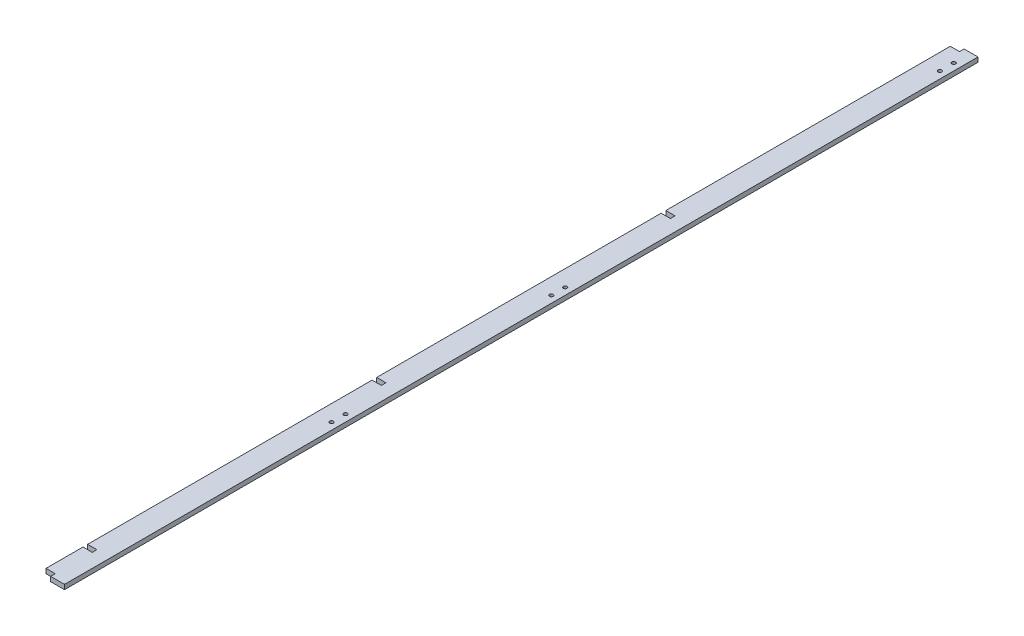
SolidWorks part; units mm, degrees
material "轻木"
ref_plane "前视基准面" through (0, 0, 0) normal (0, 0, 1) x (1, 0, 0)
ref_plane "上视基准面" through (0, 0, 0) normal (0, 1, 0) x (1, 0, 0)
ref_plane "右视基准面" through (0, 0, 0) normal (1, 0, 0) x (0, 0, -1)
other "Configuration Table"
sketch "草图1" plane through (0, 0, 1160.01) normal (0, 0, 1) x (1, 0, 0)
  line L1 (130.7876, -3.3897) -> (120.7876, -3.3897)
  line L2 (130.7876, -3.3897) -> (130.7876, -5.3897)
  line L3 (130.7876, -5.3897) -> (120.7876, -5.3897)
  line L4 (120.7876, -3.3897) -> (120.7876, -5.3897)
  dimension "D1" = 2
  dimension "D2" = 10
extrude "凸台-拉伸1" add sketch "草图1" against normal blind 395
sketch "草图2" plane through (0, -3.3897, 0) normal (0, 1, 0) x (1, 0, 0)
  line L0 (120.7876, -890.01) -> (124.7876, -890.01)
  line L9 (120.7876, -890.01) -> (120.7876, -892.01)
  line L22 (120.7876, -892.01) -> (124.7876, -892.01)
  line L23 (120.7876, -765.01) -> (124.7876, -765.01)
  line L28 (120.7876, -765.01) -> (120.7876, -767.01)
  line L29 (120.7876, -767.01) -> (124.7876, -767.01)
  line L30 (124.7876, -890.01) -> (124.7876, -892.01)
  line L39 (124.7876, -765.01) -> (124.7876, -767.01)
  line L40 (120.7876, -1015.01) -> (124.7876, -1015.01)
  line L41 (120.7876, -1015.01) -> (120.7876, -1017.01)
  line L42 (120.7876, -1017.01) -> (124.7876, -1017.01)
  line L43 (124.7876, -1015.01) -> (124.7876, -1017.01)
  line L44 (120.7876, -1140.01) -> (124.7876, -1140.01)
  line L45 (120.7876, -1140.01) -> (120.7876, -1142.01)
  line L46 (120.7876, -1142.01) -> (124.7876, -1142.01)
  line L47 (124.7876, -1140.01) -> (124.7876, -1142.01)
  line L48 (120.7876, -765.01) -> (120.7876, -890.01) construction
  line L49 (130.7876, -1160.01) -> (120.7876, -1160.01) construction
  line L50 (124.7876, -1160.01) -> (120.7876, -1160.01)
  line L51 (124.7876, -1160.01) -> (124.7876, -1158.01)
  line L52 (124.7876, -1158.01) -> (120.7876, -1158.01)
  line L53 (120.7876, -1160.01) -> (120.7876, -1158.01)
  line L54 (120.7876, -765.01) -> (120.7876, -1160.01) construction
  line L55 (130.7876, -765.01) -> (120.7876, -765.01) construction
  line L56 (130.7876, -765.01) -> (130.7876, -1160.01) construction
  line L57 (127.7876, -772.51) -> (127.7876, -940.51) construction
  line L58 (127.7876, -946.51) -> (127.7876, -1041.51) construction
  circle A0 centre (127.7876, -772.51) radius 0.8
  circle A1 centre (127.7876, -778.51) radius 0.8
  circle A2 centre (127.7876, -940.51) radius 0.8
  circle A3 centre (127.7876, -946.51) radius 0.8
  circle A4 centre (127.7876, -1041.51) radius 0.8
  circle A5 centre (127.7876, -1035.51) radius 0.8
  dimension "D9" = 1.6
  dimension "D10" = 1.6
  dimension "D2" = 2
  dimension "D4" = 4
  dimension "D1" = 4
  dimension "D3" = 125
  dimension "D5" = 2
  dimension "D6" = 4
  dimension "D7" = 7.5
  dimension "D8" = 3
  dimension "D11" = 6
  dimension "D12" = 168
  dimension "D14" = 95
  dimension "D13" = 2
extrude "切除-拉伸1" cut sketch "草图2" against normal through all
